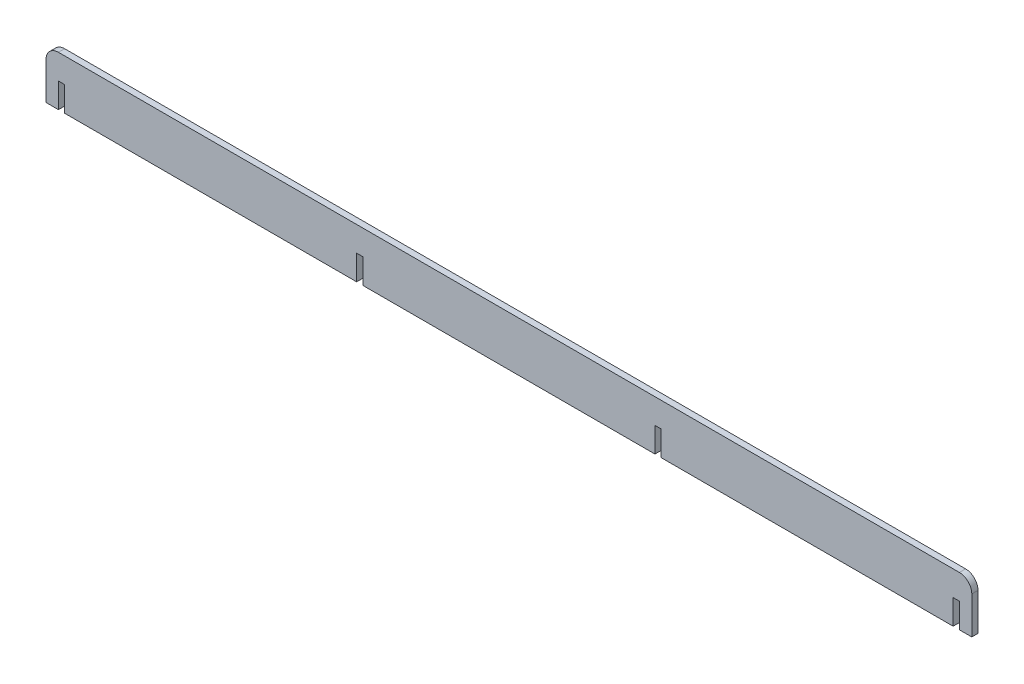
SolidWorks part; units mm, degrees
material "Oak"
ref_plane "Front Plane" through (0, 0, 0) normal (0, 0, 1) x (1, 0, 0)
ref_plane "Top Plane" through (0, 0, 0) normal (0, 1, 0) x (1, 0, 0)
ref_plane "Right Plane" through (0, 0, 0) normal (1, 0, 0) x (0, 0, -1)
sketch "Sketch1" plane through (0, 0, 0) normal (0, 0, 1) x (1, 0, 0)
  line L0 (2.5, -265.4469) -> (-722.5, -265.4469) construction
  line L1 (-360, -265.4469) -> (-360, -245.4469) construction
  line L3 (-732.5, -225.4469) -> (12.5, -225.4469)
  line L4 (-732.5, -225.4469) -> (-732.5, -265.4469)
  line L5 (-732.5, -265.4469) -> (12.5, -265.4469)
  line L6 (12.5, -225.4469) -> (12.5, -265.4469)
  line L7 (-732.5, -225.4469) -> (12.5, -265.4469) construction
  line L8 (-732.5, -265.4469) -> (12.5, -225.4469) construction
  line L25 (-722.5, -265.4469) -> (-722.5, -245.4469)
  line L26 (-722.5, -245.4469) -> (-717.5, -245.4469)
  line L27 (-717.5, -245.4469) -> (-717.5, -265.4469)
  line L28 (-717.5, -265.4469) -> (-722.5, -265.4469)
  line L29 (-482.5, -265.4469) -> (-482.5, -245.4469)
  line L30 (-482.5, -245.4469) -> (-477.5, -245.4469)
  line L31 (-477.5, -245.4469) -> (-477.5, -265.4469)
  line L32 (-477.5, -265.4469) -> (-482.5, -265.4469)
  line L33 (-242.5, -265.4469) -> (-242.5, -245.4469)
  line L34 (-242.5, -245.4469) -> (-237.5, -245.4469)
  line L35 (-237.5, -245.4469) -> (-237.5, -265.4469)
  line L36 (-237.5, -265.4469) -> (-242.5, -265.4469)
  line L37 (-2.5, -265.4469) -> (-2.5, -245.4469)
  line L38 (-2.5, -245.4469) -> (2.5, -245.4469)
  line L39 (2.5, -245.4469) -> (2.5, -265.4469)
  line L40 (2.5, -265.4469) -> (-2.5, -265.4469)
  dimension "D2" = 40
extrude "Boss-Extrude1" add sketch "Sketch1" along normal blind 5 contours L38 L39 L5 L6 L3 L4 L25 L26 L27 L29 L30 L31 L33 L34 L35 L37
fillet "Fillet1" radius 10 2 edges at (12.5, -225.4469, 2.5) (-732.5, -225.4469, 2.5)
